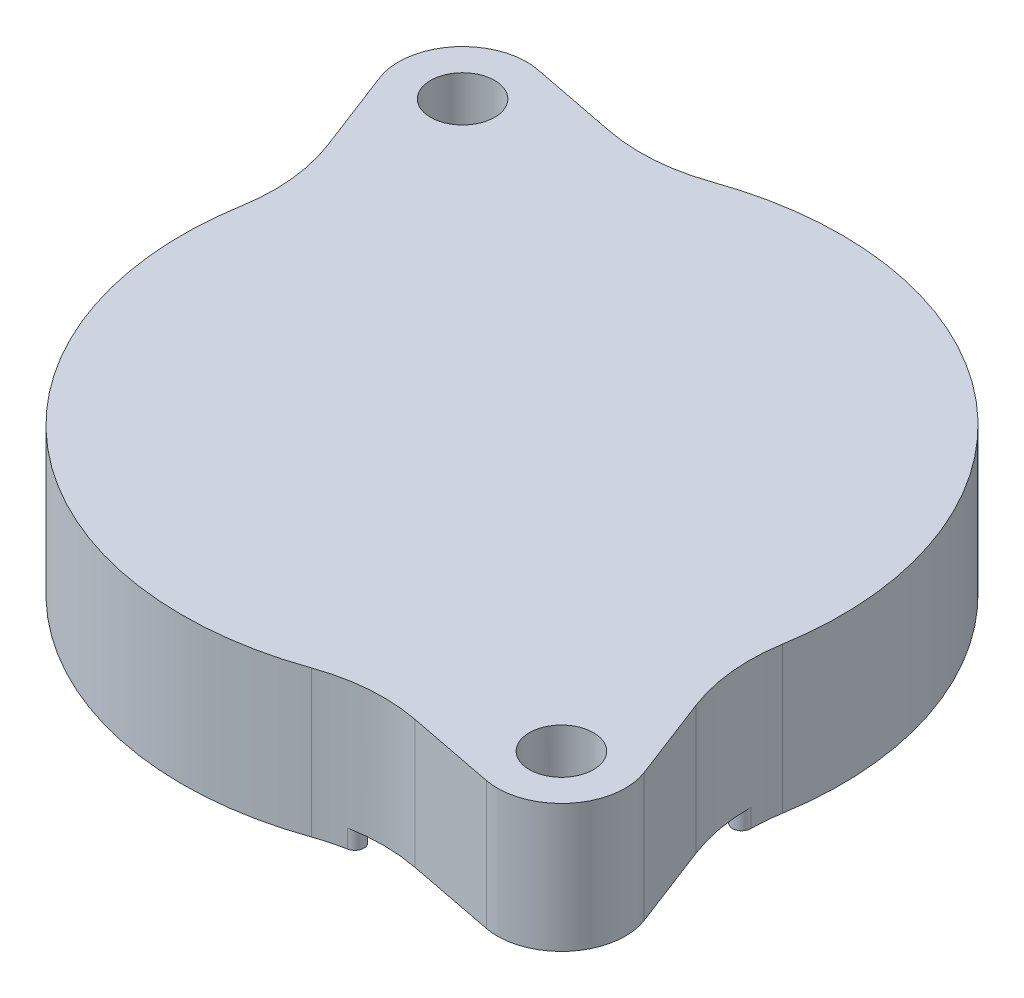
SolidWorks part; units mm, degrees
ref_plane "Front" through (0, 0, 0) normal (0, 0, 1) x (1, 0, 0)
ref_plane "Top" through (0, 0, 0) normal (0, 1, 0) x (1, 0, 0)
ref_plane "Right" through (0, 0, 0) normal (1, 0, 0) x (0, 0, -1)
ref_plane "Plane1" through (0, 0.5, 0) normal (0, -1, 0) x (1, 0, 0)
sketch "Sketch1" plane through (0, 0.5, 0) normal (0, -1, 0) x (1, 0, 0)
  line L0 (-18.2775, -8.2211) -> (-20.0439, -12.8228)
  line L1 (-16.1085, -17.5127) -> (-11.2701, -16.5722)
  line L2 (18.2775, 8.2211) -> (20.0439, 12.8228)
  line L3 (16.1085, 17.5127) -> (11.2701, 16.5722)
  line L4 (-16.7764, -14.077) -> (16.7764, 14.077) construction
  line L5 (0, 0) -> (13.3011, 0) construction
  line L6 (0, 0) -> (8.5383, -10.1755) construction
  arc A0 (11.2701, 16.5722) -> (6.0184, 16.964) centre (9.362, 26.3885) cw
  arc A1 (6.0184, 16.964) -> (-17.7514, -2.9812) centre (0, 0) ccw
  arc A2 (-17.7514, -2.9812) -> (-18.2775, -8.2211) centre (-27.6133, -4.6374) cw
  arc A3 (-20.0439, -12.8228) -> (-16.1085, -17.5127) centre (-16.7764, -14.077) ccw
  arc A4 (-11.2701, -16.5722) -> (-6.0184, -16.964) centre (-9.362, -26.3885) cw
  arc A5 (-6.0184, -16.964) -> (17.7514, 2.9812) centre (0, 0) ccw
  arc A6 (17.7514, 2.9812) -> (18.2775, 8.2211) centre (27.6133, 4.6374) cw
  arc A7 (20.0439, 12.8228) -> (16.1085, 17.5127) centre (16.7764, 14.077) ccw
  dimension "D1" = 18
  dimension "D4" = 3.5
  dimension "D5" = 10
  dimension "D2" = 40
  dimension "D3" = 43.8
  dimension "D6" = 58
extrude "Boss-Extrude1" add sketch "Sketch1" against normal blind 7
sketch "Sketch2" plane through (0, 0.5, 0) normal (0, -1, 0) x (1, 0, 0)
  line L0 (-7.7931, -15.677) -> (-7.4004, -15.3476)
  line L1 (16.3995, 4.6229) -> (16.7921, 4.9524)
  line L2 (7.7931, 15.677) -> (7.4004, 15.3476)
  line L3 (-16.3995, -4.6229) -> (-16.7921, -4.9524)
  line L4 (0, 0) -> (16.7764, 14.077) construction
  arc A0 (-7.5617, -16.5519) -> (-7.7931, -15.677) centre (-7.4717, -16.0601) cw
  arc A1 (-7.4004, -15.3476) -> (-6.8739, -15.2746) centre (-7.079, -15.7306) cw
  arc A2 (-6.8739, -15.2746) -> (16.2362, 4.117) centre (0, 0) ccw
  arc A3 (16.2362, 4.117) -> (16.3995, 4.6229) centre (16.7209, 4.2399) cw
  arc A4 (16.7921, 4.9524) -> (17.6135, 4.5726) centre (17.1135, 4.5694) cw
  arc A5 (17.6135, 4.5726) -> (17.7514, 2.9812) centre (27.6133, 4.6374) ccw
  arc A6 (17.7514, 2.9812) -> (-6.0184, -16.964) centre (0, 0) cw
  arc A7 (-6.0184, -16.964) -> (-7.5617, -16.5519) centre (-9.362, -26.3885) ccw
  arc A8 (-17.7514, -2.9812) -> (6.0184, 16.964) centre (0, 0) cw
  arc A9 (6.0184, 16.964) -> (7.5617, 16.5519) centre (9.362, 26.3885) ccw
  arc A10 (7.5617, 16.5519) -> (7.7931, 15.677) centre (7.4717, 16.0601) cw
  arc A11 (7.4004, 15.3476) -> (6.8739, 15.2746) centre (7.079, 15.7306) cw
  arc A12 (6.8739, 15.2746) -> (-16.2362, -4.117) centre (0, 0) ccw
  arc A13 (-16.2362, -4.117) -> (-16.3995, -4.6229) centre (-16.7209, -4.2399) cw
  arc A14 (-16.7921, -4.9524) -> (-17.6135, -4.5726) centre (-17.1135, -4.5694) cw
  arc A15 (-17.6135, -4.5726) -> (-17.7514, -2.9812) centre (-27.6133, -4.6374) ccw
  arc A16 (-6.0184, -16.964) -> (17.7514, 2.9812) centre (0, 0) ccw construction
  arc A17 (18.2775, 8.2211) -> (17.7514, 2.9812) centre (27.6133, 4.6374) ccw construction
  arc A18 (6.0184, 16.964) -> (11.2701, 16.5722) centre (9.362, 26.3885) ccw construction
  arc A19 (-18.2775, -8.2211) -> (-17.7514, -2.9812) centre (-27.6133, -4.6374) ccw construction
  arc A20 (-6.0184, -16.964) -> (-11.2701, -16.5722) centre (-9.362, -26.3885) ccw construction
  dimension "D1" = 1.25
  dimension "D2" = 0.5
  dimension "D3" = 14
extrude "Boss-Extrude2" add sketch "Sketch2" along normal blind 1
sketch "Sketch3" plane through (0, 7.5, 0) normal (0, 1, 0) x (-1, 0, 0)
  circle A0 centre (-16.7764, 14.077) radius 1.75
  arc A2 (-16.1085, 17.5127) -> (-20.0439, 12.8228) centre (-16.7764, 14.077) ccw construction
  circle A3 centre (16.7764, -14.077) radius 1.75
  dimension "D1" = 3.5
extrude "Cut-Extrude1" cut sketch "Sketch3" against normal through all
